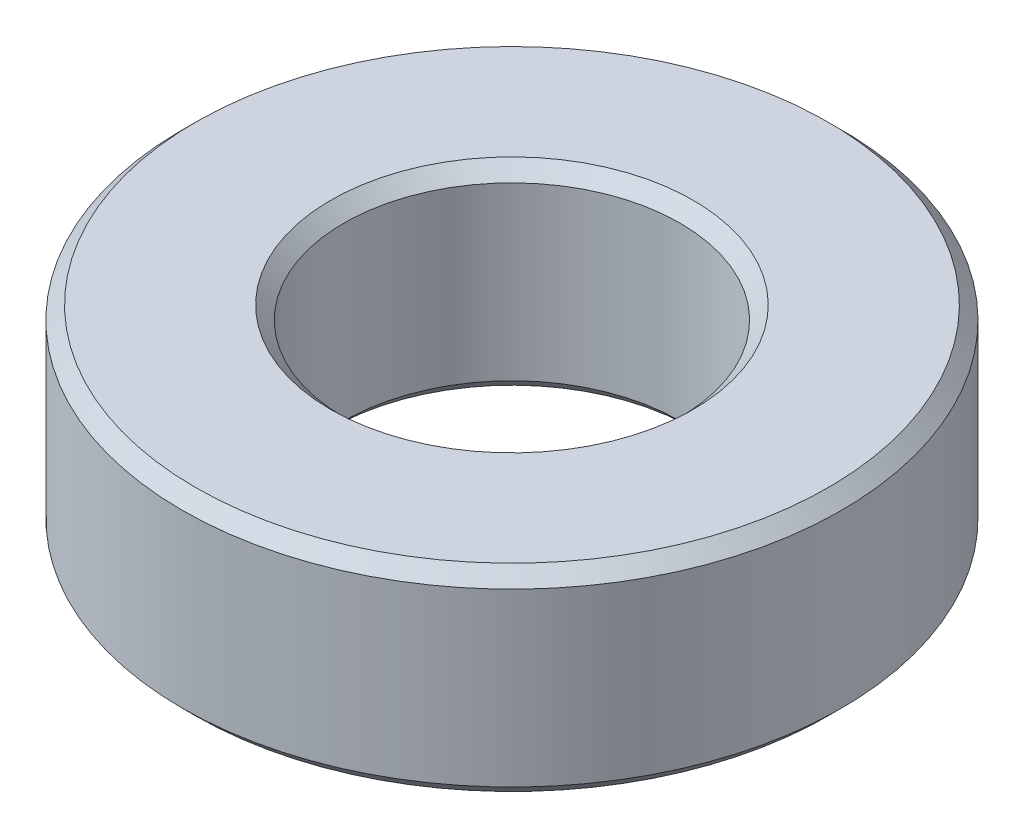
SolidWorks part; units mm, degrees
material "6061-T6 (SS)"
ref_plane "Front Plane" through (0, 0, 0) normal (0, 0, 1) x (1, 0, 0)
ref_plane "Top Plane" through (0, 0, 0) normal (0, 1, 0) x (1, 0, 0)
ref_plane "Right Plane" through (0, 0, 0) normal (1, 0, 0) x (0, 0, -1)
sketch "Sketch1" plane through (0, 0, 0) normal (1, 0, 0) x (0, 0, -1)
  line L0 (0, 2.1339) -> (0, -2.1339) construction
  line L1 (2.55, 1.3) -> (2.75, 1.5)
  line L2 (2.75, 1.5) -> (4.8, 1.5)
  line L3 (2.55, 1.3) -> (2.55, -1.3)
  line L4 (2.75, -1.5) -> (4.8, -1.5)
  line L5 (5, 1.3) -> (5, -1.3)
  line L6 (2.55, 1.5) -> (5, -1.5) construction
  line L7 (2.55, -1.5) -> (5, 1.5) construction
  line L8 (4.8, 1.5) -> (5, 1.3)
  line L9 (4.8, -1.5) -> (5, -1.3)
  line L10 (2.55, -1.3) -> (2.75, -1.5)
  point P0 (3.775, 0)
  point P4 (0, 0)
  dimension "D1" = 2.45
  dimension "D2" = 3
  dimension "D3" = 2.55
revolve "Revolve1" add sketch "Sketch1" angle 360 about L0
